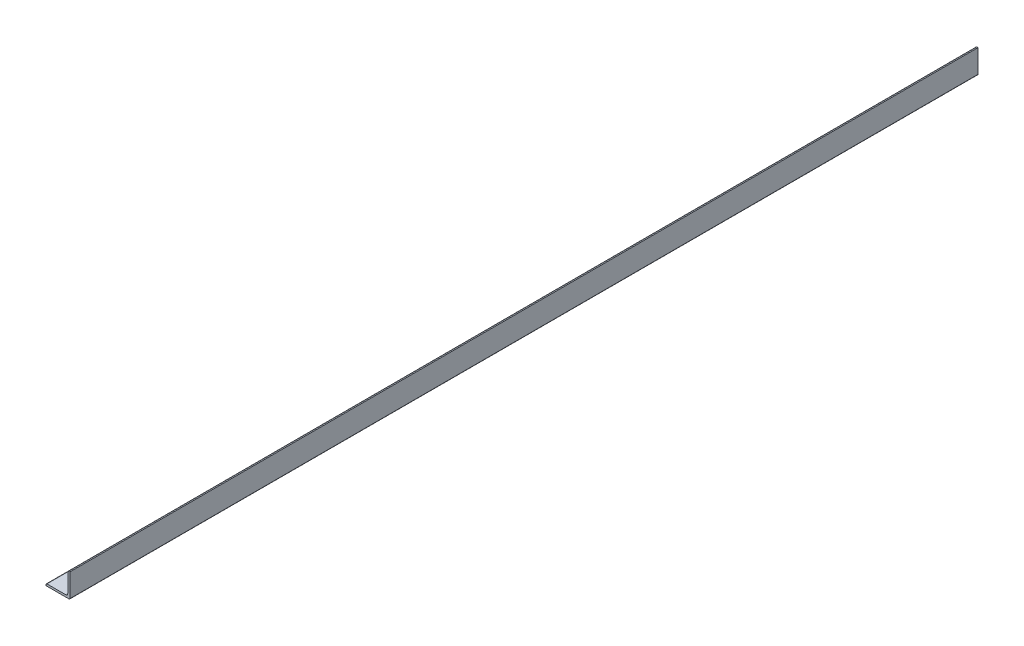
SolidWorks part; units mm, degrees
ref_plane "Front Plane" through (0, 0, 0) normal (0, 0, 1) x (1, 0, 0)
ref_plane "Top Plane" through (0, 0, 0) normal (0, 1, 0) x (1, 0, 0)
ref_plane "Right Plane" through (0, 0, 0) normal (1, 0, 0) x (0, 0, -1)
sketch "Sketch1" plane through (0, 0, 0) normal (0, 0, 1) x (1, 0, 0)
  line L0 (-3, 6) -> (-3, 35)
  line L1 (-1, 0) -> (-35, 0)
  line L2 (0, 1) -> (0, 35)
  line L3 (0, 35) -> (-35, 35) construction
  line L4 (-35, 0) -> (-35, 35) construction
  line L5 (0, 0) -> (-35, 35) construction
  line L6 (0, 35) -> (-35, 0) construction
  line L7 (0, 0) -> (-3, 0) construction
  line L8 (0, 0) -> (0, 3) construction
  line L9 (0, 3) -> (-3, 3) construction
  line L10 (-3, 0) -> (-3, 3) construction
  line L11 (0, 0) -> (-3, 3) construction
  line L12 (0, 3) -> (-3, 0) construction
  line L13 (-3, 35) -> (0, 35)
  line L14 (-6, 3) -> (-35, 3)
  line L15 (-35, 3) -> (-35, 0)
  line L16 (-35, 0) -> (-35.3886, -0.0241)
  arc A0 (-3, 6) -> (-6, 3) centre (-6, 6) cw
  arc A1 (-1, 0) -> (0, 1) centre (-1, 1) ccw
  point P5 (-17.5, 17.5)
  point P9 (-1.5, 1.5)
  dimension "D3" = 3
  dimension "D4" = 1
  dimension "D1" = 3
  dimension "D2" = 35
extrude "Boss-Extrude1" add sketch "Sketch1" along normal blind 668 contours L1 A1 L2 L13 L0 A0 L14 L15
fillet "Fillet1" radius 1.5 2 edges at (-35, 3, 334) (-3, 35, 334)
mirror "Mirror4" about plane through (0, 0, 0) normal (0, 0, 1) of bodies 101 104
